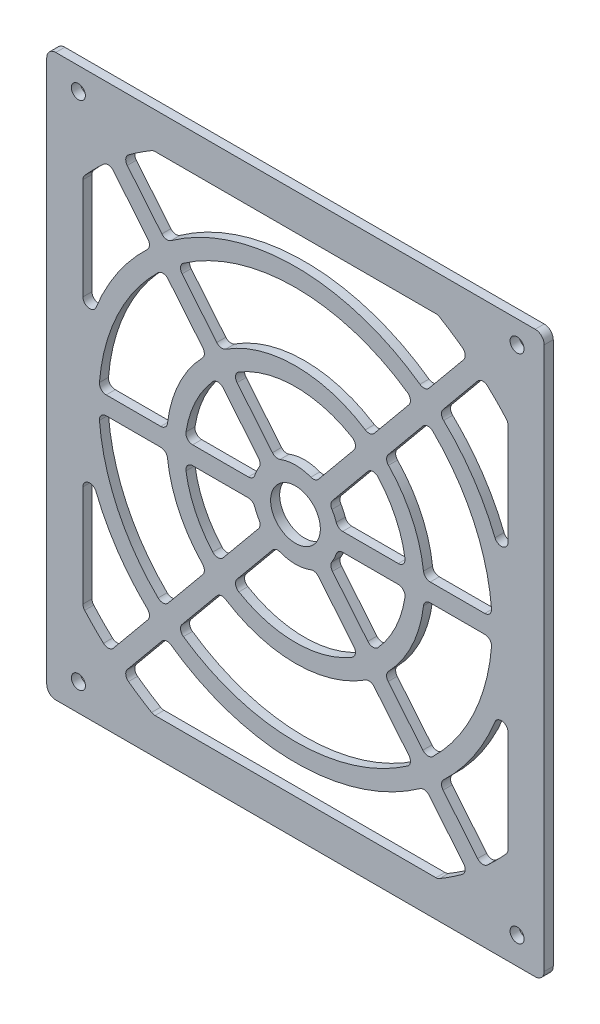
SolidWorks part; units mm, degrees
material "Thornel Mat VMA"
ref_plane "前视基准面" through (0, 0, 0) normal (0, 0, 1) x (1, 0, 0)
ref_plane "上视基准面" through (0, 0, 0) normal (0, 1, 0) x (1, 0, 0)
ref_plane "右视基准面" through (0, 0, 0) normal (1, 0, 0) x (0, 0, -1)
sketch "草图1" plane through (0, 0, 0) normal (0, 0, 1) x (1, 0, 0)
  line L1 (-55, -62) -> (55, -62)
  line L2 (-55, -62) -> (-55, 62)
  line L3 (-55, 62) -> (55, 62)
  line L4 (55, -62) -> (55, 62)
  line L5 (0, 62) -> (0, -62) construction
  line L6 (-55, 0) -> (55, 0) construction
  point P0 (0, 0)
  dimension "D1" = 110
  dimension "D2" = 124
extrude "凸台-拉伸1" add sketch "草图1" along normal blind 2
sketch "草图2" plane through (0, 0, 2) normal (0, 0, 1) x (1, 0, 0)
  line L0 (-9.6516, 9.303) -> (-9.6516, 36.303) construction
  line L1 (-8.3526, 8.553) -> (15.8961, 22.553) construction
  line L2 (-8.3526, 7.053) -> (15.8961, -6.947) construction
  line L3 (-9.6516, 6.303) -> (-9.6516, -21.697) construction
  line L4 (-10.9506, 7.053) -> (-35.1994, -6.947) construction
  line L5 (-10.9506, 8.553) -> (-35.1994, 22.553) construction
  line L6 (-9.9506, 10.2851) -> (-34.1994, 24.2851)
  line L7 (-11.9506, 8.7851) -> (-36.1994, -5.2149)
  line L8 (-11.6516, 6.303) -> (-11.6516, -21.697)
  line L9 (-9.3526, 5.321) -> (14.8961, -8.679)
  line L10 (-7.6516, 9.303) -> (-7.6516, 36.303)
  line L11 (-11.9506, 6.821) -> (-36.1994, 20.821)
  line L12 (-9.9506, 5.321) -> (-34.1994, -8.679)
  line L13 (-7.6516, 6.303) -> (-7.6516, -21.697)
  line L14 (-7.3526, 8.7851) -> (16.8961, -5.2149)
  line L15 (-11.6516, 9.303) -> (-11.6516, 36.303)
  line L16 (-7.3526, 6.821) -> (16.8961, 20.821)
  line L17 (-9.3526, 10.2851) -> (14.8961, 24.2851)
  circle A0 centre (-9.6516, 7.803) radius 28 construction
  circle A1 centre (-9.6516, 7.803) radius 20
  circle A2 centre (-9.6516, 7.803) radius 20 construction
  circle A3 centre (-9.6516, 7.803) radius 1.5
  circle A4 centre (-9.6516, 7.803) radius 5.5
  circle A5 centre (-9.6516, 7.803) radius 13.5
  circle A6 centre (-9.6516, 7.803) radius 16.5
  circle A7 centre (-9.6516, 7.803) radius 24.5
  circle A8 centre (-9.6516, 7.803) radius 28.5 construction
  point P24 (-9.6516, 7.803)
  dimension "D3" = 3
  dimension "D1" = 0
  dimension "D2" = 8
  dimension "D4" = 4
  dimension "D5" = 8
  dimension "D6" = 3
  dimension "D7" = 8
  dimension "D8" = 4
  dimension "D10" = 2
  dimension "D11" = 2
  dimension "D12" = 2
  dimension "D13" = 2
  dimension "D9" = 6
sketch "草图3" plane through (0, 0, 2) normal (0, 0, 1) x (1, 0, 0)
  line L0 (-55, -62) -> (55, -62) construction
  line L1 (55, 62) -> (-55, 62) construction
  line L2 (55, -62) -> (55, 62) construction
  circle A4 centre (49, 57) radius 1.25 construction
  circle A5 centre (49, -56) radius 1.25 construction
  circle A6 centre (-48, -56) radius 1.25 construction
  circle A7 centre (-48, 57) radius 1.25 construction
  circle A8 centre (49, 57) radius 1.55
  circle A9 centre (-48, 57) radius 1.55
  circle A10 centre (-48, -56) radius 1.55
  circle A11 centre (49, -56) radius 1.55
  dimension "D1" = 3.1
  dimension "D2" = 6
  dimension "D3" = 5
  dimension "D4" = 97
  dimension "D5" = 6
extrude "切除-拉伸1" cut sketch "草图3" against normal blind 10
extrude "切除-拉伸2" [suppressed] cut sketch "草图2" against normal blind 10 contours A3 | L15 A5 L6 A4 | L17 A5 L10 A4 | L14 A5 L16 A4 | L13 A5 L9 A4 | L12 A5 L8 A4 | L11 A5 L7 A4 | L11 A7 L7 A6 | L15 A7 L6 A6 | L17 A7 L10 A6 | L14 A7 L16 A6 | L13 A7 L9 A6 | L12 A7 L8 A6
fillet "圆角1" [suppressed] radius 1.1
sketch "草图4" [suppressed] plane through (0, 0, 2) normal (0, 0, 1) x (1, 0, 0)
  circle A0 centre (-9.6516, 7.803) radius 3.25
  dimension "D1" = 6.5
extrude "切除-拉伸3" [suppressed] cut sketch "草图4" against normal blind 10
fillet "圆角2" radius 2 4 edges at (55, -62, 1) (-55, -62, 1) (-55, 62, 1) (55, 62, 1)
sketch "草图5" plane through (0, 0, 2) normal (0, 0, 1) x (1, 0, 0)
  line L0 (-47, 53) -> (-47, -52)
  line L1 (-47, -52) -> (-44, -52)
  line L2 (-44, -52) -> (-44, -54)
  line L3 (-44, -54) -> (45, -54)
  line L4 (45, -54) -> (45, -52)
  line L5 (45, -52) -> (47, -52)
  line L6 (47, -52) -> (47, 53)
  line L7 (47, 53) -> (45, 53)
  line L8 (45, 53) -> (45, 54)
  line L9 (45, 54) -> (-44, 54)
  line L10 (-44, 54) -> (-44, 53)
  line L11 (-44, 53) -> (-47, 53)
  line L12 (-53, -62) -> (53, -62) construction
  line L13 (-55, 60) -> (-55, -60) construction
  line L14 (53, 62) -> (-53, 62) construction
  line L15 (55, -60) -> (55, 60) construction
  circle A0 centre (0, 0) radius 9.5
  circle A1 centre (0, 0) radius 24.5
  circle A2 centre (0, 0) radius 28.5
  circle A3 centre (0, 0) radius 5.5
  circle A4 centre (0, 0) radius 43.5
  circle A5 centre (0, 0) radius 47.5
  circle A6 centre (0, 0) radius 62.5
  circle A7 centre (49, -56) radius 1.55 construction
  circle A8 centre (-48, -56) radius 1.55 construction
  circle A9 centre (-48, 57) radius 1.55 construction
  circle A10 centre (49, 57) radius 1.55 construction
  dimension "D3" = 11
  dimension "D1" = 15
  dimension "D2" = 4
  dimension "D4" = 4
  dimension "D5" = 15
  dimension "D6" = 4
  dimension "D7" = 15
  dimension "D8" = 4
  dimension "D9" = 4
  dimension "D10" = 8
  dimension "D11" = 8
  dimension "D12" = 4
  dimension "D13" = 4
  dimension "D14" = 4
  dimension "D15" = 4
  dimension "D16" = 4
  dimension "D17" = 4
  dimension "D18" = 8
  dimension "D19" = 8
extrude "切除-拉伸4" cut sketch "草图5" against normal up to surface (2 mm away) contours L6 A6 L9 L0 A5 | A4 A2 | A1 A0 | L0 A6 L3 L6 A5 | A3 up to face at (47.45, -56, 0)
sketch "草图6" plane through (0, 0, 2) normal (0, 0, 1) x (1, 0, 0)
  line L0 (-39.7529, -48.2282) -> (39.7529, 48.2282) construction
  line L1 (-39.7529, 48.2282) -> (39.7529, -48.2282) construction
  line L2 (-38.2096, -49.5003) -> (-1.7155, -5.2256)
  line L3 (-41.2962, 46.9561) -> (-4.8021, 2.6814)
  line L4 (-41.2962, -46.9561) -> (-4.8021, -2.6814)
  line L5 (-38.2096, 49.5003) -> (-1.7155, 5.2256)
  line L6 (4.8021, -2.6814) -> (41.2962, -46.9561)
  line L7 (-38.2096, 49.5003) -> (41.2962, -46.9561) construction
  line L8 (1.7155, -5.2256) -> (38.2096, -49.5003)
  line L9 (-41.2962, 46.9561) -> (38.2096, -49.5003) construction
  line L10 (4.8021, 2.6814) -> (41.2962, 46.9561)
  line L11 (-38.2096, -49.5003) -> (41.2962, 46.9561) construction
  line L12 (1.7155, 5.2256) -> (38.2096, 49.5003)
  line L13 (-41.2962, -46.9561) -> (38.2096, 49.5003) construction
  line L14 (-5.5, 0) -> (-55, 0) construction
  line L15 (-55, 60) -> (-55, -60) construction
  line L16 (5.5, 0) -> (55, 0) construction
  line L17 (55, -60) -> (55, 60) construction
  line L18 (5.5, -2) -> (55, -2)
  line L19 (-5.5, 2) -> (-55, 2)
  line L20 (5.5, 2) -> (55, 2)
  line L21 (-5.5, -2) -> (-55, -2)
  line L22 (5.5, -2) -> (5.5, 2)
  line L23 (55, -2) -> (55, 2)
  line L24 (-5.5, 2) -> (-5.5, -2)
  line L25 (-55, 2) -> (-55, -2)
  arc A0 (-47, -41.1977) -> (-31.4682, -54) centre (0, 0) ccw construction
  arc A1 (47, 41.1977) -> (31.4682, 54) centre (0, 0) ccw construction
  arc A2 (-31.4682, 54) -> (-47, 41.1977) centre (0, 0) ccw construction
  arc A3 (31.4682, -54) -> (47, -41.1977) centre (0, 0) ccw construction
  arc A4 (-38.2096, -49.5003) -> (-41.2962, -46.9561) centre (-39.7529, -48.2282) cw
  arc A5 (41.2962, 46.9561) -> (38.2096, 49.5003) centre (39.7529, 48.2282) ccw
  arc A6 (-41.2962, 46.9561) -> (-38.2096, 49.5003) centre (-39.7529, 48.2282) cw
  arc A7 (38.2096, -49.5003) -> (41.2962, -46.9561) centre (39.7529, -48.2282) ccw
  circle A8 centre (0, 0) radius 5.5 construction
  circle A9 centre (0, 0) radius 5.5
  circle M16 centre (0, 0) radius 43.5
  arc M18 (-31.4682, -54) -> (-47, -41.1977) centre (0, 0) cw
  arc M20 (-47, -6.8739) -> (47, -6.8739) centre (0, 0) ccw
  arc M22 (47, -41.1977) -> (31.4682, -54) centre (0, 0) cw
  arc M24 (31.4682, 54) -> (47, 41.1977) centre (0, 0) cw
  arc M26 (47, 6.8739) -> (-47, 6.8739) centre (0, 0) ccw
  arc M28 (-47, 41.1977) -> (-31.4682, 54) centre (0, 0) cw
  dimension "D1" = 2
  dimension "D2" = 2
  dimension "D3" = 2
  dimension "D4" = 2
extrude "凸台-拉伸2" add sketch "草图6" against normal up to surface (2 mm away) contours A9 L4 L2 M16 | L4 L2 M18 M20 | L24 L19 L21 M16 | L22 L18 L20 M16 | A9 L8 L6 M16 | L8 L6 M20 M22 | A9 L10 L12 M16 | L12 L10 M26 M24 | A9 L5 L3 M16 | L5 L3 M28 M26 up to face at (-24.5, 0, 0)
fillet "圆角3" radius 1.5 76 edges at (28.6421, 37.893, 1) (-28.6421, 37.893, 1) (-38.1892, 49.4756, 1) (31.4682, 54, 1) (-31.4682, 54, 1) (38.1892, 49.4756, 1) (31.7287, -35.3488, 1) (47, 6.8739, 1) (47, -6.8739, 1) (47, 41.1977, 1) (47, -41.1977, 1) (41.2758, -46.9314, 1) (-47, 6.8739, 1) (-47, -6.8739, 1) (-31.7287, -35.3488, 1) (-19.6259, -20.6657, 1) (-29.182, -32.2592, 1) (-43.454, -2, 1) (-28.4297, -2, 1) (-9.2871, -2, 1) (-7.4503, -5.8943, 1) (-17.0744, -17.5703, 1) (-24.4182, -2, 1) (28.4297, -2, 1) (43.454, -2, 1) (29.182, -32.2592, 1) (19.6259, -20.6657, 1) (26.0954, -34.8034, 1) (-26.0954, -34.8034, 1) (-16.5393, -23.2099, 1) (16.5393, -23.2099, 1) (7.4503, -5.8943, 1) (9.2871, -2, 1) (24.4182, -2, 1) (17.0744, -17.5703, 1) (-13.9878, -20.1144, 1) (-4.3637, -8.4385, 1) (4.3637, -8.4385, 1) (13.9878, -20.1144, 1) (-31.4682, -54, 1) (31.4682, -54, 1) (-38.1892, -49.4756, 1) (-28.6421, -37.893, 1) (28.6421, -37.893, 1) (38.1892, -49.4756, 1) (29.182, 32.2592, 1) (43.454, 2, 1) (28.4297, 2, 1) (19.6259, 20.6657, 1) (24.4182, 2, 1) (9.2871, 2, 1) (7.4503, 5.8943, 1) (17.0744, 17.5703, 1) (31.7287, 35.3488, 1) (41.2758, 46.9314, 1) (-26.0954, 34.8034, 1) (26.0954, 34.8034, 1) (16.5393, 23.2099, 1) (-16.5393, 23.2099, 1) (13.9878, 20.1144, 1) (4.3637, 8.4385, 1) (-4.3637, 8.4385, 1) (-13.9878, 20.1144, 1) (-7.4503, 5.8943, 1) (-9.2871, 2, 1) (-24.4182, 2, 1) (-17.0744, 17.5703, 1) (-28.4297, 2, 1) (-43.454, 2, 1) (-29.182, 32.2592, 1) (-19.6259, 20.6657, 1) (-47, 41.1977, 1) (-47, -41.1977, 1) (-41.2758, 46.9314, 1) (-31.7287, 35.3488, 1) (-41.2758, -46.9314, 1)
equation "\"D5@草图5\"=\"D1@草图5\""
equation "\"D7@草图5\"=\"D1@草图5\""
equation "\"D11@草图5\"=\"D19@草图5\""
equation "\"D10@草图5\"=\"D19@草图5\""
equation "\"D18@草图5\"=\"D19@草图5\""
